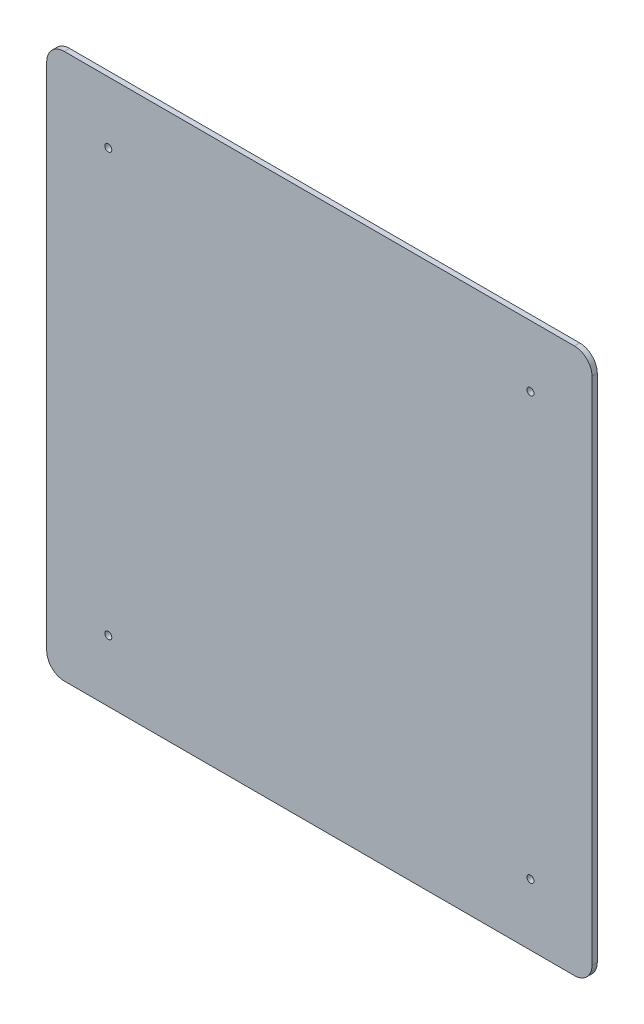
SolidWorks part; units mm, degrees
ref_plane "前视基准面" through (0, 0, 0) normal (0, 0, 1) x (1, 0, 0)
ref_plane "上视基准面" through (0, 0, 0) normal (0, 1, 0) x (1, 0, 0)
ref_plane "右视基准面" through (0, 0, 0) normal (1, 0, 0) x (0, 0, -1)
sketch "草图1" plane through (0, 0, 0) normal (0, 0, 1) x (1, 0, 0)
  line L1 (-157.583, 164.4373) -> (132.417, 164.4373)
  line L2 (-167.583, 154.4373) -> (-167.583, -135.5627)
  line L3 (-157.583, -145.5627) -> (132.417, -145.5627)
  line L4 (142.417, 154.4373) -> (142.417, -135.5627)
  line L5 (-167.583, 164.4373) -> (142.417, -145.5627) construction
  line L6 (-167.583, -145.5627) -> (142.417, 164.4373) construction
  line L11 (-132.583, 129.4373) -> (107.417, -110.5627) construction
  line L12 (-132.583, -110.5627) -> (107.417, 129.4373) construction
  circle A0 centre (107.417, 129.4373) radius 2
  circle A1 centre (107.417, -110.5627) radius 2
  circle A2 centre (-132.583, 129.4373) radius 2
  circle A3 centre (-132.583, -110.5627) radius 2
  arc A4 (132.417, -145.5627) -> (142.417, -135.5627) centre (132.417, -135.5627) ccw
  arc A5 (-167.583, -135.5627) -> (-157.583, -145.5627) centre (-157.583, -135.5627) ccw
  arc A6 (-157.583, 164.4373) -> (-167.583, 154.4373) centre (-157.583, 154.4373) ccw
  arc A7 (132.417, 164.4373) -> (142.417, 154.4373) centre (132.417, 154.4373) cw
  point P0 (-12.583, 9.4373)
  point P5 (-12.583, 9.4373)
  dimension "D4" = 10
  dimension "D1" = 310
  dimension "D2" = 310
  dimension "D3" = 240
extrude "凸台-拉伸1" add sketch "草图1" along normal blind 3
